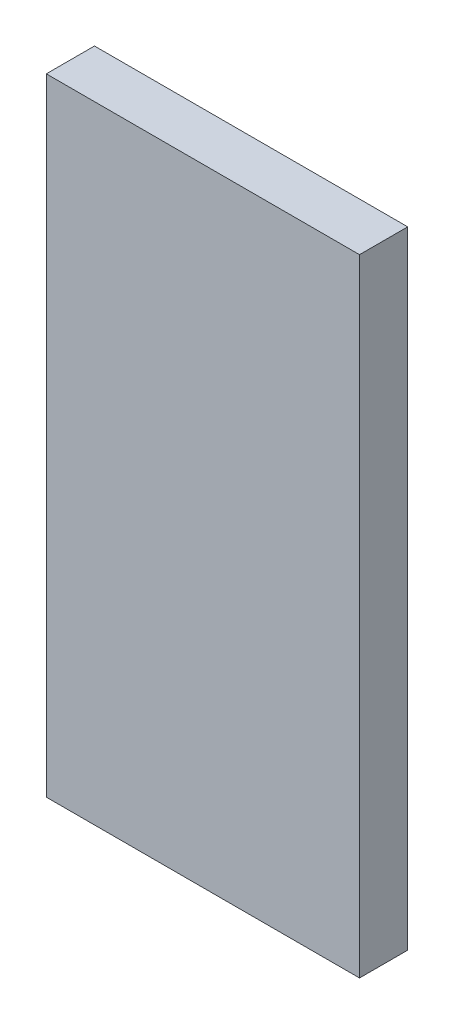
SolidWorks part; units mm, degrees
material "MDF"
ref_plane "Front Plane" through (0, 0, 0) normal (0, 0, 1) x (1, 0, 0)
ref_plane "Top Plane" through (0, 0, 0) normal (0, 1, 0) x (1, 0, 0)
ref_plane "Right Plane" through (0, 0, 0) normal (1, 0, 0) x (0, 0, -1)
sketch "Sketch1" plane through (0, 0, 0) normal (0, 0, 1) x (1, 0, 0)
  line L1 (-41.275, -82.55) -> (41.275, -82.55)
  line L2 (-41.275, -82.55) -> (-41.275, 82.55)
  line L3 (-41.275, 82.55) -> (41.275, 82.55)
  line L4 (41.275, -82.55) -> (41.275, 82.55)
  line L5 (-41.275, -82.55) -> (41.275, 82.55) construction
  line L6 (-41.275, 82.55) -> (41.275, -82.55) construction
  point P0 (0, 0)
  dimension "D1" = 165.1
  dimension "D2" = 82.55
extrude "Boss-Extrude1" add sketch "Sketch1" along normal blind 12.7
